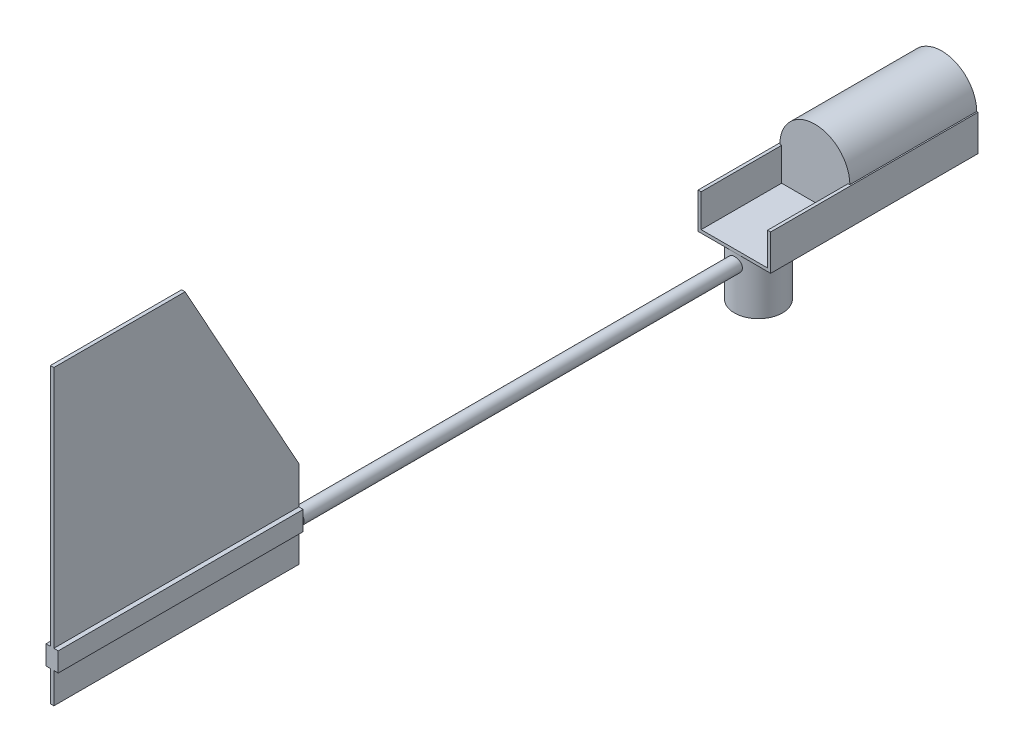
SolidWorks part; units mm, degrees
ref_plane "Přední rovina" through (0, 0, 0) normal (0, 0, 1) x (1, 0, 0)
ref_plane "Horní rovina" through (0, 0, 0) normal (0, 1, 0) x (1, 0, 0)
ref_plane "Pravá rovina" through (0, 0, 0) normal (1, 0, 0) x (0, 0, -1)
sketch "Skica1" plane through (0, 0, 0) normal (0, 0, 1) x (1, 0, 0)
  line L0 (0, 0) -> (0, -41) construction
  line L1 (-41.5, -41) -> (41.5, -41)
  line L2 (-41.5, -41) -> (-41.5, 0)
  line L3 (-41.5, 0) -> (-40, 0)
  line L4 (41.5, -41) -> (41.5, 0)
  line L5 (41.5, 0) -> (40, 0)
  line L6 (-40, 0) -> (40, 0) construction
  circle A0 centre (0, 0) radius 40
  dimension "D1" = 80
  dimension "D2" = 83
  dimension "D3" = 41
extrude "Přidat vysunutím1" add sketch "Skica1" along normal blind 145 contours A0 L3 L2 L1 L4 L5
sketch "Skica2" plane through (0, 0, 145) normal (0, 0, 1) x (1, 0, 0)
  line L0 (-41.5, 0) -> (-38, 0)
  line L1 (-38, 0) -> (-38, -37.5)
  line L2 (-38, -37.5) -> (38, -37.5)
  line L3 (38, -37.5) -> (38, 0)
  line L4 (38, 0) -> (41.5, 0)
  line L5 (41.5, 0) -> (41.5, -41)
  line L6 (41.5, -41) -> (-41.5, -41)
  line L7 (-41.5, -41) -> (-41.5, 0)
  dimension "D1" = 3.5
  dimension "D2" = 3.5
  dimension "D3" = 3.5
extrude "Přidat vysunutím2" add sketch "Skica2" along normal blind 92
sketch "Skica3" plane through (0, -41, 0) normal (0, -1, 0) x (1, 0, 0)
  line L0 (-41.5, 237) -> (41.5, 237) construction
  circle A0 centre (0, 209.5) radius 27.5
  dimension "D1" = 55
extrude "Přidat vysunutím3" add sketch "Skica3" along normal blind 60
sketch "Skica4" plane through (0, 0, 237) normal (0, 0, 1) x (1, 0, 0)
  line L0 (0, -41) -> (41.5, -41) construction
  line L1 (0, -101) -> (0, -53) construction
  line L2 (-27.5, -101) -> (27.5, -101) construction
  circle A0 centre (0, -53) radius 8
  dimension "D1" = 16
  dimension "D2" = 12
extrude "Přidat vysunutím4" add sketch "Skica4" along normal blind 500 and the other way blind 40
sketch "Skica5" plane through (0, 0, 0) normal (1, 0, 0) x (0, 0, -1)
  line L0 (-737, 1) -> (-737, -99)
  line L1 (-737, -99) -> (-1017, -99)
  line L2 (-1017, -99) -> (-1017, 236)
  line L3 (-1017, 236) -> (-867, 236)
  line L4 (-867, 236) -> (-737, 1)
  line L5 (-737, -61) -> (-237, -61) construction
  line L6 (-737, -45) -> (-737, -61) construction
  dimension "D1" = 100
  dimension "D2" = 38
  dimension "D3" = 280
  dimension "D4" = 335
  dimension "D5" = 150
extrude "Přidat vysunutím5" add sketch "Skica5" along normal blind 2 and the other way blind 2
sketch "Skica6" plane through (2, 0, 0) normal (1, 0, 0) x (0, 0, -1)
  line L0 (-737, -45.254) -> (-737, 1) construction
  line L1 (-737, -42) -> (-1017, -42)
  line L2 (-737, -42) -> (-737, -64)
  line L3 (-737, -64) -> (-1017, -64)
  line L4 (-1017, -42) -> (-1017, -64)
  line L5 (-1017, 236) -> (-1017, -99) construction
  line L6 (-737, -60.746) -> (-737, -45.254) construction
  point P8 (-737, -53)
  dimension "D1" = 22
extrude "Přidat vysunutím6" add sketch "Skica6" along normal blind 5
mirror "Zrcadlit1" about plane through (0, 0, 0) normal (1, 0, 0) of "Přidat vysunutím6"
